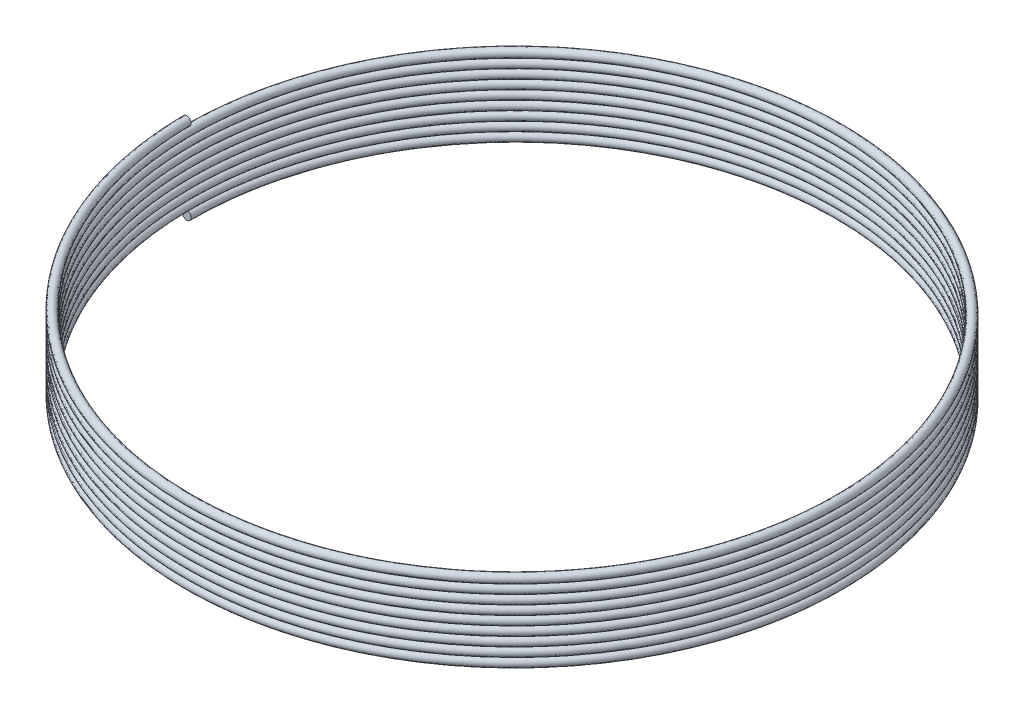
SolidWorks part; units mm, degrees
ref_plane "Front Plane" through (0, 0, 0) normal (0, 0, 1) x (1, 0, 0)
ref_plane "Top Plane" through (0, 0, 0) normal (0, 1, 0) x (1, 0, 0)
ref_plane "Right Plane" through (0, 0, 0) normal (1, 0, 0) x (0, 0, -1)
sketch "Sketch1" plane through (0, 0, 0) normal (0, 1, 0) x (1, 0, 0)
  circle A0 centre (0, 0) radius 17 construction
  circle A1 centre (0, 0) radius 17.5
  circle A2 centre (0, 0) radius 16.5
  dimension "D3" = 35
  dimension "D1" = 0.5
  dimension "D2" = 0.5
sketch "Sketch2" plane through (0, 0, 0) normal (0, 1, 0) x (1, 0, 0)
  circle A0 centre (0, 0) radius 17 construction
  circle A1 centre (0, 0) radius 17
curve "Helix/Spiral1" pitch 0.475 height 4.275 turns 9
sweep "Sweep1" add path "Helix/Spiral1" circular profile diameter 0.455 parameters "D3"=0.455
ref_plane "Plane1" through (0, -0.2, 0) normal (0, 1, 0) x (1, 0, 0)
